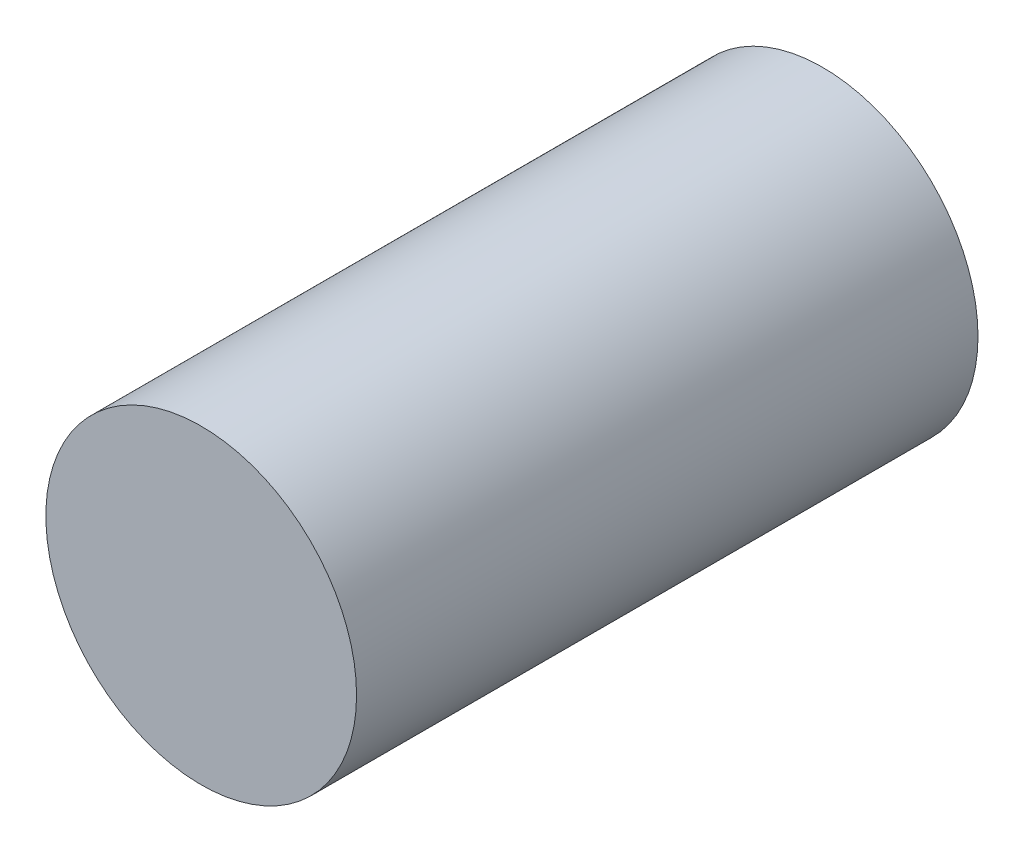
SolidWorks part; units mm, degrees
ref_plane "正面" through (0, 0, 0) normal (0, 0, 1) x (1, 0, 0)
ref_plane "平面" through (0, 0, 0) normal (0, 1, 0) x (1, 0, 0)
ref_plane "右側面" through (0, 0, 0) normal (1, 0, 0) x (0, 0, -1)
sketch "ｽｹｯﾁ1" plane through (0, 0, 0) normal (0, 0, 1) x (1, 0, 0)
  circle A0 centre (0, 0) radius 50
extrude "ﾎﾞｽ - 押し出し1" add sketch "ｽｹｯﾁ1" along normal blind 200
